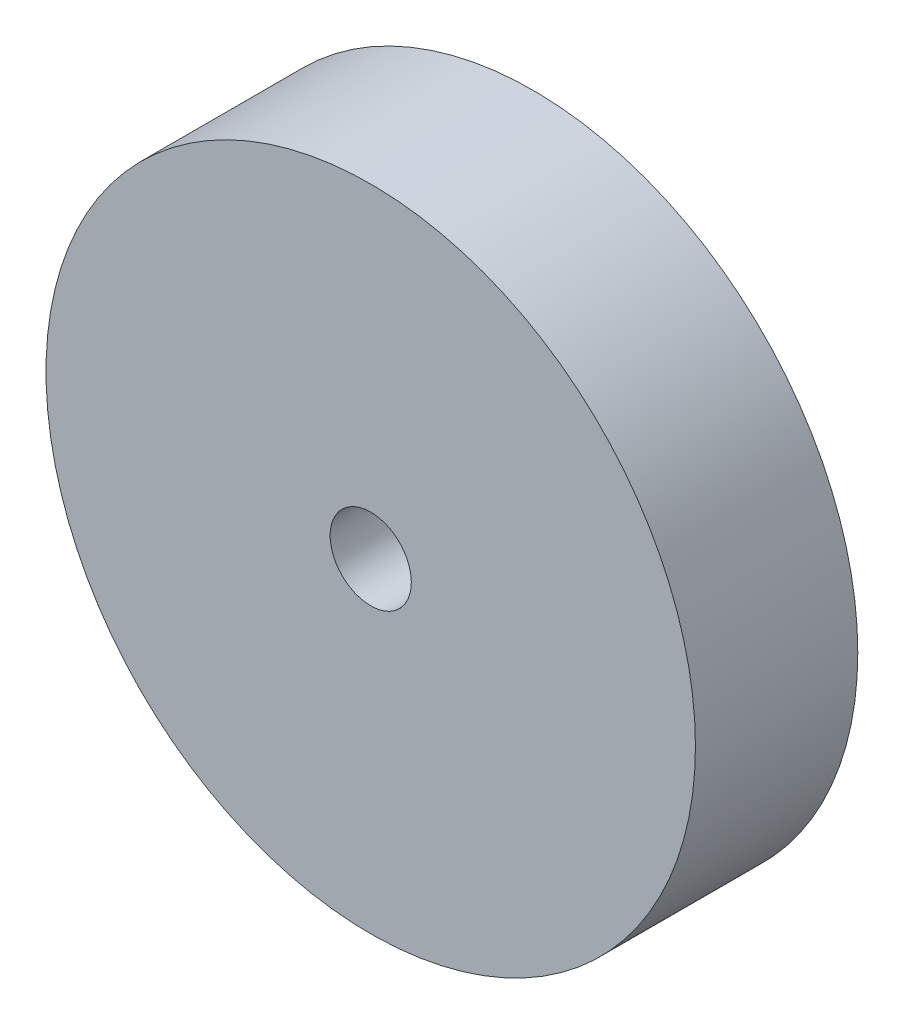
SolidWorks part; units mm, degrees
ref_plane "Front Plane" through (0, 0, 0) normal (0, 0, 1) x (1, 0, 0)
ref_plane "Top Plane" through (0, 0, 0) normal (0, 1, 0) x (1, 0, 0)
ref_plane "Right Plane" through (0, 0, 0) normal (1, 0, 0) x (0, 0, -1)
sketch "Sketch1" plane through (0, 0, 0) normal (0, 0, 1) x (1, 0, 0)
  circle A0 centre (0, 0) radius 4
  circle A1 centre (0, 0) radius 0.5
  dimension "D1" = 8
  dimension "D2" = 1
extrude "Boss-Extrude1" add sketch "Sketch1" along normal blind 2
